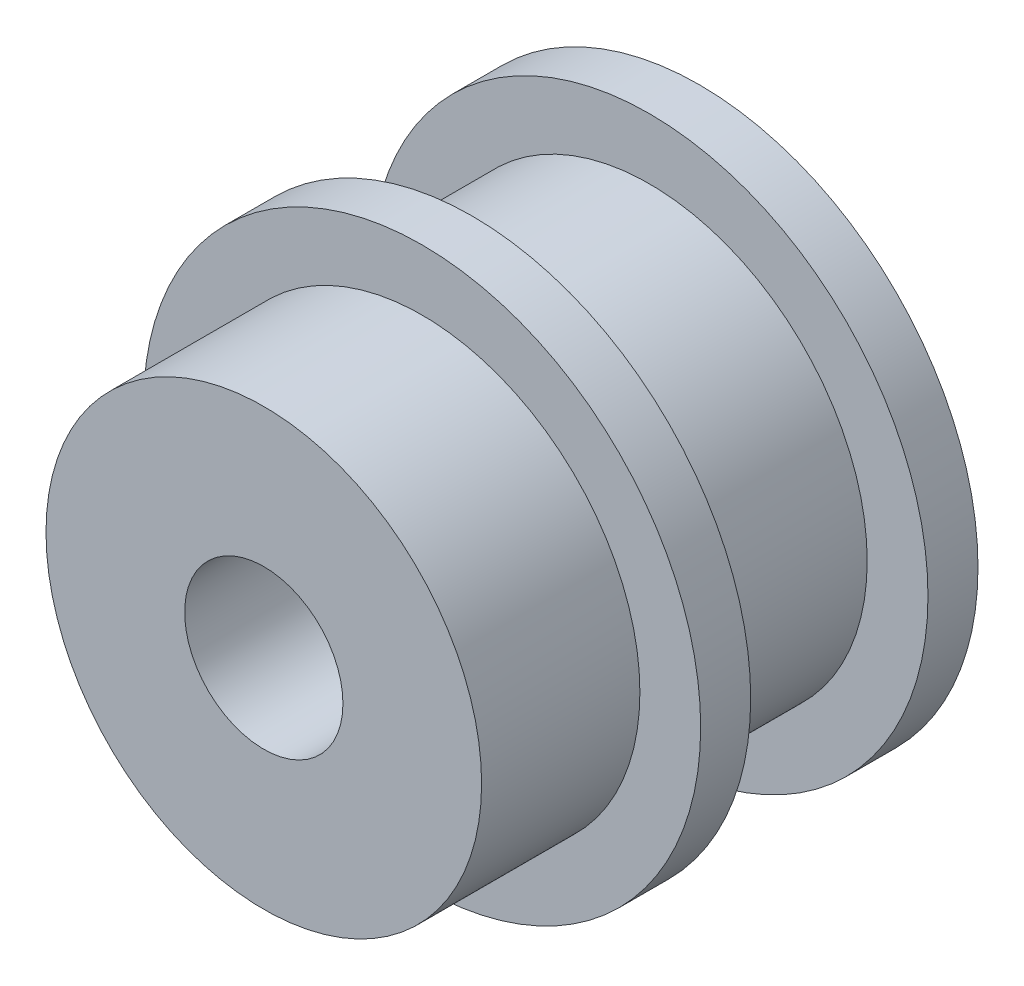
SolidWorks part; units mm, degrees
ref_plane "Front Plane" through (0, 0, 0) normal (0, 0, 1) x (1, 0, 0)
ref_plane "Top Plane" through (0, 0, 0) normal (0, 1, 0) x (1, 0, 0)
ref_plane "Right Plane" through (0, 0, 0) normal (1, 0, 0) x (0, 0, -1)
sketch "Sketch1" plane through (0, 0, 0) normal (1, 0, 0) x (0, 0, -1)
  line L0 (0, 0) -> (17.4752, 0) construction
  line L1 (0, -8.7376) -> (0, 0)
  line L2 (0, 8.7376) -> (6.35, 8.7376)
  line L3 (6.35, 8.7376) -> (6.35, 11.176)
  line L4 (6.35, 11.176) -> (8.3566, 11.176)
  line L5 (8.3566, 11.176) -> (8.3566, 8.7376)
  line L6 (8.3566, 8.7376) -> (15.4686, 8.7376)
  line L7 (15.4686, 8.7376) -> (15.4686, 11.176)
  line L8 (15.4686, 11.176) -> (17.4752, 11.176)
  line L9 (17.4752, 11.176) -> (17.4752, 0)
  line L10 (0, 3.175) -> (17.4752, 3.175)
  line L11 (0, -3.175) -> (17.4752, -3.175)
  line L12 (15.4686, -11.176) -> (17.4752, -11.176)
  line L13 (15.4686, -8.7376) -> (15.4686, -11.176)
  line L14 (8.3566, -8.7376) -> (15.4686, -8.7376)
  line L15 (8.3566, -11.176) -> (8.3566, -8.7376)
  line L16 (6.35, -11.176) -> (8.3566, -11.176)
  line L17 (6.35, -8.7376) -> (6.35, -11.176)
  line L18 (0, -8.7376) -> (6.35, -8.7376)
  line L19 (0, 0) -> (0, 8.7376)
  line L20 (17.4752, 0) -> (17.4752, -11.176)
  dimension "D1" = 6.35
  dimension "D2" = 17.4752
  dimension "D3" = 22.352
  dimension "D4" = 11.1252
  dimension "D5" = 7.112
  dimension "D6" = 17.4752
revolve "Revolve5" add sketch "Sketch1" angle 360 about L0
